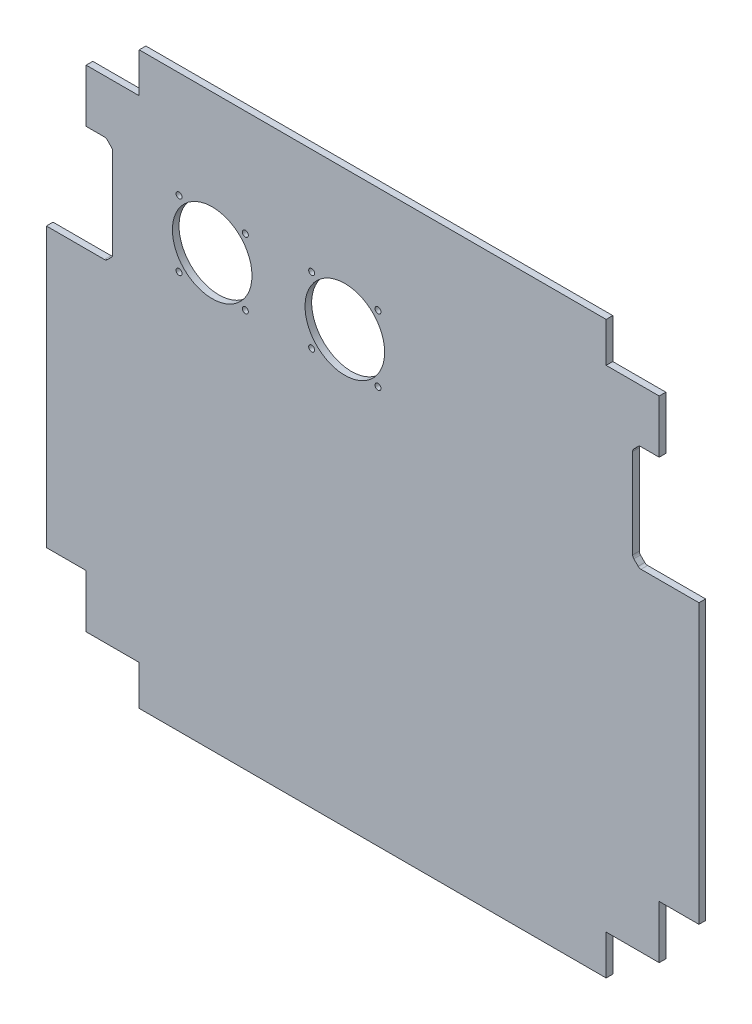
SolidWorks part; units mm, degrees
material "Acrílico (Impacto medio-alto)"
ref_plane "Alzado" through (0, 0, 0) normal (0, 0, 1) x (1, 0, 0)
ref_plane "Planta" through (0, 0, 0) normal (0, 1, 0) x (1, 0, 0)
ref_plane "Vista lateral" through (0, 0, 0) normal (1, 0, 0) x (0, 0, -1)
sketch "Croquis1" plane through (0, 0, 0) normal (0, 0, 1) x (1, 0, 0)
  line L0 (-246, 0) -> (246, 0)
  line L1 (0, 0) -> (0, 215) construction
  line L2 (-246, -145) -> (-246, 145)
  line L3 (-246, 145) -> (-216, 145)
  line L4 (-216, 145) -> (-216, 185)
  line L5 (-216, 185) -> (-176, 185)
  line L6 (-176, 185) -> (-176, 215)
  line L7 (-176, 215) -> (176, 215)
  line L8 (246, -145) -> (246, 145)
  line L9 (246, 145) -> (216, 145)
  line L10 (216, 145) -> (216, 185)
  line L11 (216, 185) -> (176, 185)
  line L12 (176, 185) -> (176, 215)
  line L13 (-246, -145) -> (-216, -145)
  line L14 (-216, -145) -> (-216, -185)
  line L15 (-216, -185) -> (-176, -185)
  line L16 (-176, -185) -> (-176, -215)
  line L17 (-176, -215) -> (176, -215)
  line L18 (176, -185) -> (176, -215)
  line L19 (216, -185) -> (176, -185)
  line L20 (216, -145) -> (216, -185)
  line L21 (246, -145) -> (216, -145)
  point P4 (0, 0)
  dimension "D1" = 492
  dimension "D2" = 145
  dimension "D3" = 216
  dimension "D4" = 176
  dimension "D5" = 30
  dimension "D6" = 40
extrude "Saliente-Extruir1" add sketch "Croquis1" along normal blind 5 contours L1 L0 L8 L9 L10 L11 L12 L7 | L0 L1 L7 L6 L5 L4 L3 L2 | L21 L8 L0 L2 L13 L14 L15 L16 L17 L18 L19 L20
sketch "Croquis3" plane through (0, 0, 5) normal (0, 0, 1) x (1, 0, 0)
  line L1 (-246, 145) -> (-196, 145)
  line L2 (-246, 145) -> (-246, 65)
  line L3 (-246, 65) -> (-196, 65)
  line L4 (-196, 145) -> (-196, 65)
  line L5 (246, 145) -> (196, 145)
  line L6 (246, 145) -> (246, 65)
  line L7 (246, 65) -> (196, 65)
  line L8 (196, 145) -> (196, 65)
  dimension "D1" = 50
  dimension "D2" = 80
  dimension "D3" = 50
  dimension "D4" = 80
extrude "Cortar-Extruir2" cut sketch "Croquis3" against normal blind 10 contours L2 L1 L4 L3 | L6 L5 L8 L7
chamfer "Chaflán1" distance 5 angle 45 4 edges at (-196, 65, 2.5) (-196, 145, 2.5) (196, 65, 2.5) (196, 145, 2.5)
fillet "Redondeo1" radius 3 8 edges at (196, 140, 2.5) (201, 145, 2.5) (201, 65, 2.5) (196, 70, 2.5) (-196, 140, 2.5) (-201, 145, 2.5) (-201, 65, 2.5) (-196, 70, 2.5)
sketch "Croquis4" plane through (0, 0, 5) normal (0, 0, 1) x (1, 0, 0)
  line L0 (-216, 145) -> (-216, 185) construction
  line L1 (-176, 215) -> (176, 215) construction
  circle A0 centre (-146, 135) radius 2.25
  circle A1 centre (-96, 135) radius 2.25
  circle A2 centre (-146, 85) radius 2.25
  circle A3 centre (-96, 85) radius 2.25
  circle A4 centre (-46, 135) radius 2.25
  circle A5 centre (-46, 85) radius 2.25
  circle A6 centre (4, 135) radius 2.25
  circle A7 centre (4, 85) radius 2.25
  dimension "D1" = 4.5
  dimension "D8" = 4.5
  dimension "D2" = 50
  dimension "D3" = 50
  dimension "D4" = 70
  dimension "D5" = 80
  dimension "D6" = 50
  dimension "D7" = 50
extrude "Cortar-Extruir3" cut sketch "Croquis4" against normal mid plane 10
sketch "Croquis5" plane through (0, 0, 5) normal (0, 0, 1) x (1, 0, 0)
  circle A0 centre (-121, 110) radius 30
  circle A1 centre (-146, 135) radius 2.25 construction
  circle A2 centre (-146, 85) radius 2.25 construction
  circle A3 centre (-21, 110) radius 30
  circle A4 centre (-46, 135) radius 2.25 construction
  circle A5 centre (-46, 85) radius 2.25 construction
  dimension "D1" = 60
  dimension "D3" = 25
  dimension "D4" = 60
  dimension "D5" = 25
  dimension "D6" = 25
  dimension "D2" = 25
extrude "Cortar-Extruir4" cut sketch "Croquis5" against normal through all
